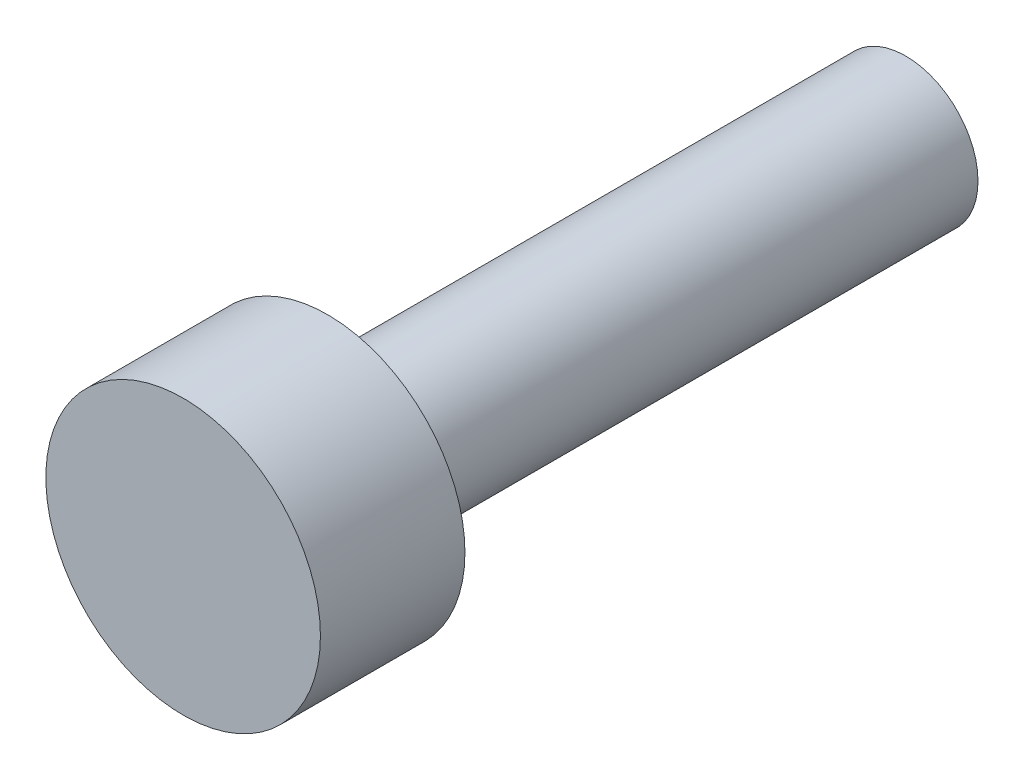
SolidWorks part; units mm, degrees
ref_plane "Front Plane" through (0, 0, 0) normal (0, 0, 1) x (1, 0, 0)
ref_plane "Top Plane" through (0, 0, 0) normal (0, 1, 0) x (1, 0, 0)
ref_plane "Right Plane" through (0, 0, 0) normal (1, 0, 0) x (0, 0, -1)
sketch "Shank_nominal_thread_envelope_profile" plane through (0, 0, 0) normal (0, 0, 1) x (1, 0, 0)
  circle A0 centre (0, 0) radius 1
  dimension "D1" = 2
extrude "Shank_nominal_thread_envelope" add sketch "Shank_nominal_thread_envelope_profile" along normal blind 8 from offset 8
sketch "Socket_head_envelope_profile" plane through (0, 0, 0) normal (0, 0, 1) x (1, 0, 0)
  circle A0 centre (0, 0) radius 1.9
  dimension "D1" = 3.8
extrude "Socket_head_envelope" add sketch "Socket_head_envelope_profile" along normal blind 2
